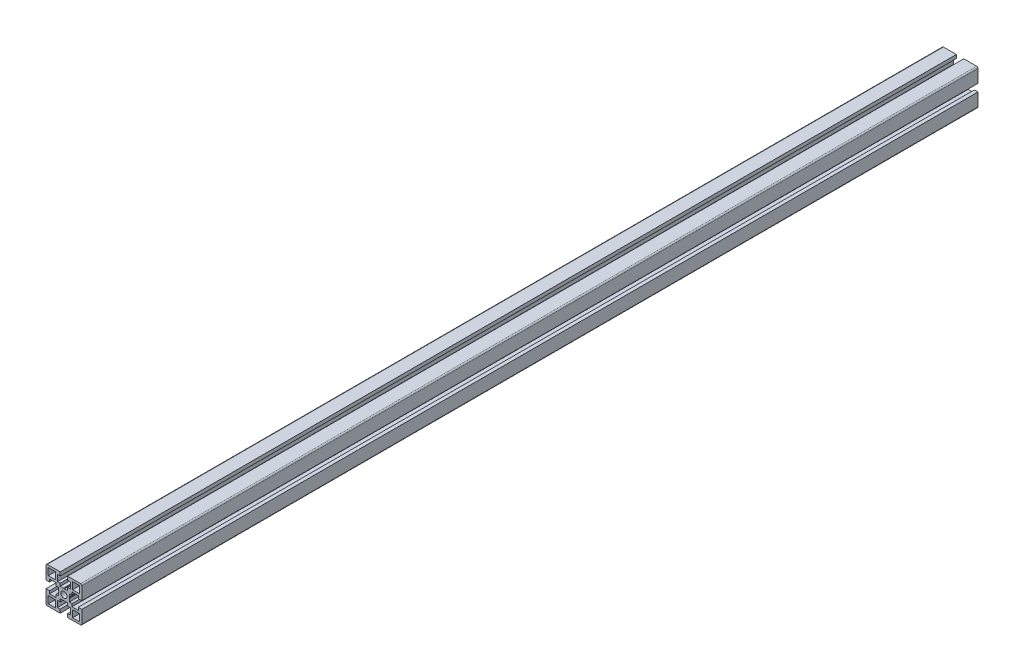
SolidWorks part; units mm, degrees
ref_plane "Front Plane" through (0, 0, 0) normal (0, 0, 1) x (1, 0, 0)
ref_plane "Top Plane" through (0, 0, 0) normal (0, 1, 0) x (1, 0, 0)
ref_plane "Right Plane" through (0, 0, 0) normal (1, 0, 0) x (0, 0, -1)
sketch "Sketch1" plane through (0, 0, 0) normal (0, 0, 1) x (1, 0, 0)
  line L0 (-17.5, 17.5) -> (-9.65, 17.5)
  line L1 (-9.65, 17.5) -> (-9.65, 9.65)
  line L2 (-9.65, 9.65) -> (-17.5, 9.65)
  line L3 (-17.5, 9.65) -> (-17.5, 17.5)
  line L4 (9.65, 17.5) -> (17.5, 17.5)
  line L5 (17.5, 17.5) -> (17.5, 9.65)
  line L6 (17.5, 9.65) -> (9.65, 9.65)
  line L7 (9.65, 9.65) -> (9.65, 17.5)
  line L8 (-9.65, -9.65) -> (-9.65, -17.5)
  line L9 (-9.65, -17.5) -> (-17.5, -17.5)
  line L10 (-17.5, -17.5) -> (-17.5, -9.65)
  line L11 (-17.5, -9.65) -> (-9.65, -9.65)
  line L12 (17.5, -17.5) -> (9.65, -17.5)
  line L13 (9.65, -17.5) -> (9.65, -9.65)
  line L14 (9.65, -9.65) -> (17.5, -9.65)
  line L15 (17.5, -9.65) -> (17.5, -17.5)
  line L16 (-7.15, 16) -> (-4.15, 16)
  line L17 (-4.15, 16) -> (-4.15, 20)
  line L18 (-4.15, 20) -> (-18.5, 20)
  line L19 (-20, 18.5) -> (-20, 4.15)
  line L20 (-20, 4.15) -> (-16, 4.15)
  line L21 (-16, 4.15) -> (-16, 7.15)
  line L22 (-16, 7.15) -> (-9, 7.15)
  line L23 (-9, 7.15) -> (-9, 4.15)
  line L24 (-9, 4.15) -> (-6, 4.15)
  line L25 (-6, 4.15) -> (-6, 0.5196)
  line L26 (-6, 0.5196) -> (-5.7, 0)
  line L27 (-5.7, 0) -> (-6, -0.5196)
  line L28 (-6, -0.5196) -> (-6, -4.15)
  line L29 (-6, -4.15) -> (-9, -4.15)
  line L30 (-9, -4.15) -> (-9, -7.15)
  line L31 (-9, -7.15) -> (-16, -7.15)
  line L32 (-16, -7.15) -> (-16, -4.15)
  line L33 (-16, -4.15) -> (-20, -4.15)
  line L34 (-20, -4.15) -> (-20, -18.5)
  line L35 (-18.5, -20) -> (-4.15, -20)
  line L36 (-4.15, -20) -> (-4.15, -16)
  line L37 (-4.15, -16) -> (-7.15, -16)
  line L38 (-7.15, -16) -> (-7.15, -9)
  line L39 (-7.15, -9) -> (-4.15, -9)
  line L40 (-4.15, -9) -> (-4.15, -6)
  line L41 (-4.15, -6) -> (-0.5196, -6)
  line L42 (-0.5196, -6) -> (0, -5.7)
  line L43 (0, -5.7) -> (0.5196, -6)
  line L44 (0.5196, -6) -> (4.15, -6)
  line L45 (4.15, -6) -> (4.15, -9)
  line L46 (4.15, -9) -> (7.15, -9)
  line L47 (7.15, -9) -> (7.15, -16)
  line L48 (7.15, -16) -> (4.15, -16)
  line L49 (4.15, -16) -> (4.15, -20)
  line L50 (4.15, -20) -> (18.5, -20)
  line L51 (20, -18.5) -> (20, -4.15)
  line L52 (20, -4.15) -> (16, -4.15)
  line L53 (16, -4.15) -> (16, -7.15)
  line L54 (16, -7.15) -> (9, -7.15)
  line L55 (9, -7.15) -> (9, -4.15)
  line L56 (9, -4.15) -> (6, -4.15)
  line L57 (6, -4.15) -> (6, -0.5196)
  line L58 (6, -0.5196) -> (5.7, 0)
  line L59 (5.7, 0) -> (6, 0.5196)
  line L60 (6, 0.5196) -> (6, 4.15)
  line L61 (6, 4.15) -> (9, 4.15)
  line L62 (9, 4.15) -> (9, 7.15)
  line L63 (9, 7.15) -> (16, 7.15)
  line L64 (16, 7.15) -> (16, 4.15)
  line L65 (16, 4.15) -> (20, 4.15)
  line L66 (20, 4.15) -> (20, 18.5)
  line L67 (18.5, 20) -> (4.15, 20)
  line L68 (4.15, 20) -> (4.15, 16)
  line L69 (4.15, 16) -> (7.15, 16)
  line L70 (7.15, 16) -> (7.15, 9)
  line L71 (7.15, 9) -> (4.15, 9)
  line L72 (4.15, 9) -> (4.15, 6)
  line L73 (4.15, 6) -> (0.5196, 6)
  line L74 (0.5196, 6) -> (0, 5.7)
  line L75 (0, 5.7) -> (-0.5196, 6)
  line L76 (-0.5196, 6) -> (-4.15, 6)
  line L77 (-4.15, 6) -> (-4.15, 9)
  line L78 (-4.15, 9) -> (-7.15, 9)
  line L79 (-7.15, 9) -> (-7.15, 16)
  circle A0 centre (0, 0) radius 3.4
  arc A1 (-18.5, 20) -> (-20, 18.5) centre (-18.5, 18.5) ccw
  arc A2 (-20, -18.5) -> (-18.5, -20) centre (-18.5, -18.5) ccw
  arc A3 (18.5, -20) -> (20, -18.5) centre (18.5, -18.5) ccw
  arc A4 (20, 18.5) -> (18.5, 20) centre (18.5, 18.5) ccw
extrude "Boss-Extrude1" add sketch "Sketch1" against normal blind 1000
